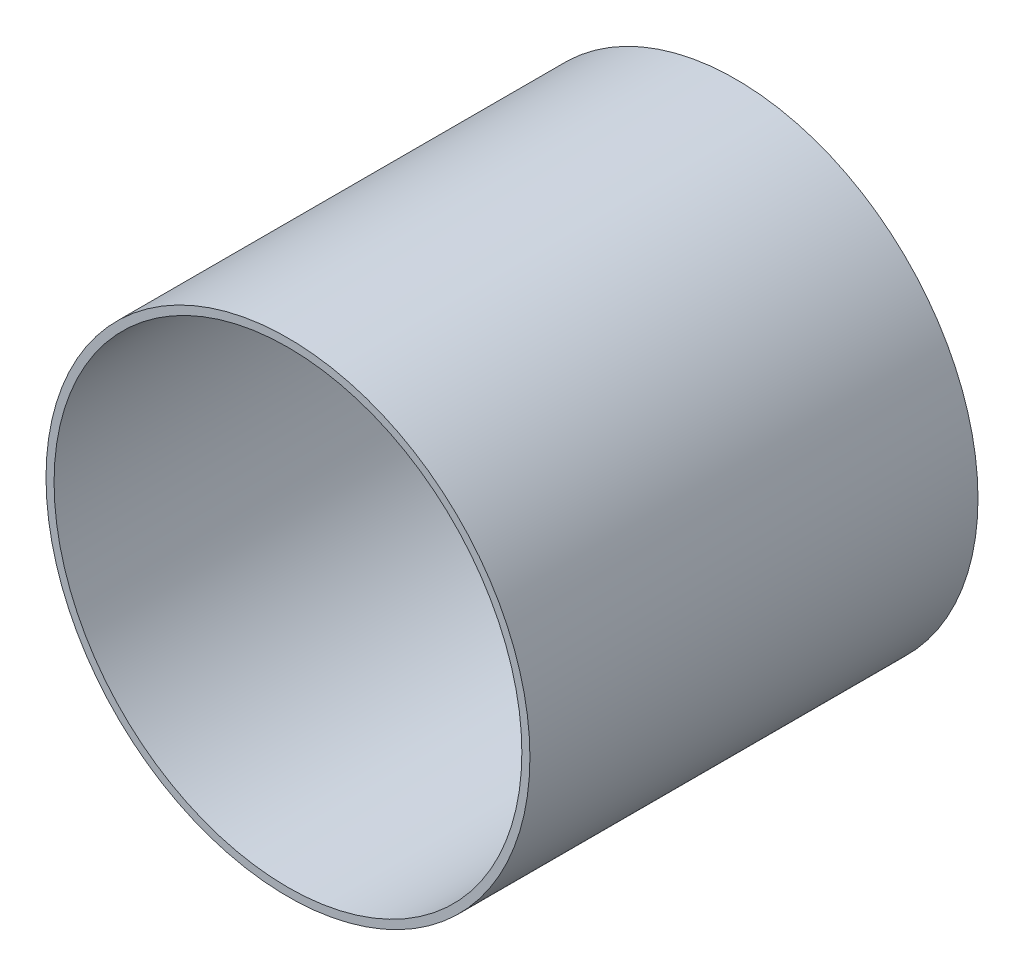
SolidWorks part; units mm, degrees
ref_plane "Front Plane" through (0, 0, 0) normal (0, 0, 1) x (1, 0, 0)
ref_plane "Top Plane" through (0, 0, 0) normal (0, 1, 0) x (1, 0, 0)
ref_plane "Right Plane" through (0, 0, 0) normal (1, 0, 0) x (0, 0, -1)
sketch "Sketch1" plane through (0, 0, 0) normal (0, 0, 1) x (1, 0, 0)
  circle A0 centre (0, 0) radius 13.05
  circle A1 centre (0, 0) radius 13.5
  dimension "D1" = 27
  dimension "D2" = 26.1
extrude "Boss-Extrude1" add sketch "Sketch1" along normal blind 25
